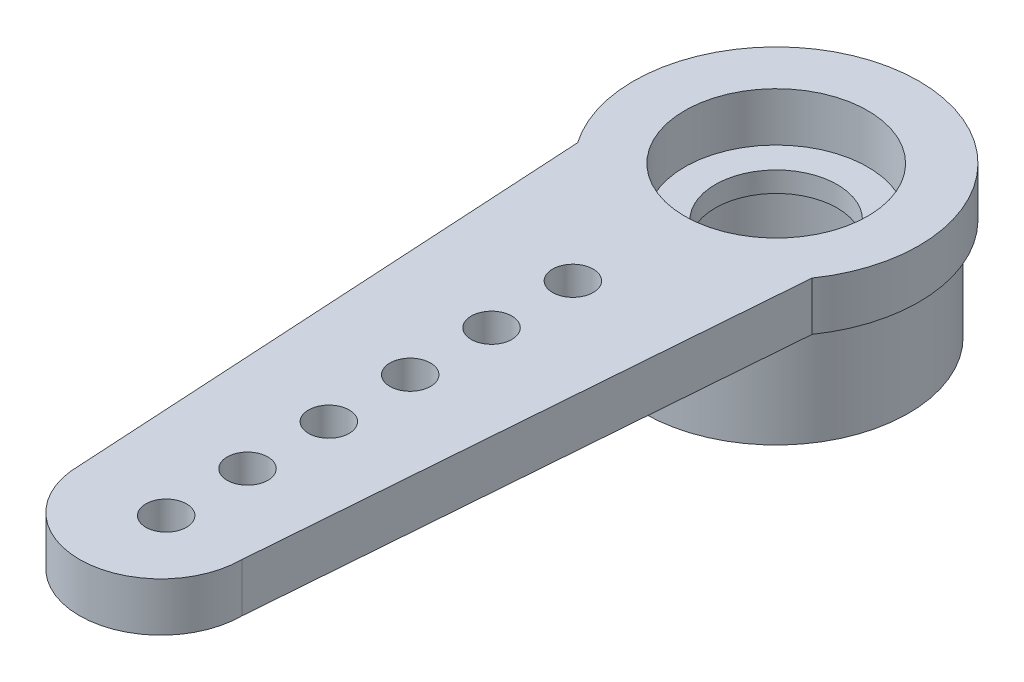
SolidWorks part; units mm, degrees
ref_plane "Front Plane" through (0, 0, 0) normal (0, 0, 1) x (1, 0, 0)
ref_plane "Top Plane" through (0, 0, 0) normal (0, 1, 0) x (1, 0, 0)
ref_plane "Right Plane" through (0, 0, 0) normal (1, 0, 0) x (0, 0, -1)
sketch "Sketch1" plane through (0, 0, 0) normal (0, 1, 0) x (1, 0, 0)
  line L0 (0, 0) -> (0, 17) construction
  line L3 (-2.8824, 2) -> (-2, 17)
  line L4 (2.8824, 2) -> (2, 17)
  line L5 (-3, 0) -> (3, 0) construction
  line L6 (-2.8824, -2) -> (-2.1324, -14.9994)
  line L7 (2.8824, -2) -> (1.8676, -15)
  line L8 (0, 0) -> (7, 0) construction
  line L9 (2.8824, 2) -> (7, 2)
  line L10 (2.8824, -2) -> (7, -2)
  line L11 (-2.8824, -2) -> (-7, -2)
  line L12 (-2.8824, 2) -> (-7, 2)
  arc A3 (2, 17) -> (-2, 17) centre (0, 17) ccw
  circle A4 centre (0, 5) radius 0.5
  circle A5 centre (0, 7) radius 0.5
  circle A6 centre (0, 9) radius 0.5
  circle A7 centre (0, 11) radius 0.5
  circle A8 centre (0, 13) radius 0.5
  circle A9 centre (0, 15) radius 0.5
  circle A10 centre (0, 17) radius 0.5
  circle A12 centre (0, -15) radius 0.5
  circle A13 centre (0, -13) radius 0.5
  circle A14 centre (0, -11) radius 0.5
  circle A15 centre (0, -9) radius 0.5
  circle A16 centre (0, -7) radius 0.5
  circle A17 centre (0, -5) radius 0.5
  arc A18 (1.8676, -15) -> (-2.1324, -14.9994) centre (-0.1324, -14.9994) cw
  arc A20 (7, -2) -> (7, 2) centre (7, 0) ccw
  circle A21 centre (7, 0) radius 0.5
  circle A22 centre (5, 0) radius 0.5
  circle A23 centre (-5, 0) radius 0.5
  circle A24 centre (-7, 0) radius 0.5
  arc A25 (-7, -2) -> (-7, 2) centre (-7, 0) cw
  circle A26 centre (0, 0) radius 2.25
  circle A27 centre (0, 0) radius 3.5083
  point P3 (0, 17.0297)
  point P38 (0, -17.0297)
  point P39 (3.5, 0)
  dimension "D2" = 2
  dimension "D5" = 1
  dimension "D8" = 2
  dimension "D10" = 1
  dimension "D11" = 1
  dimension "D13" = 4.5
  dimension "D15" = 2
  dimension "D1" = 1
  dimension "D3" = 17
  dimension "D4" = 1
  dimension "D6" = 5
  dimension "D9" = 7
  dimension "D12" = 2
  dimension "D14" = 15
  dimension "D16" = 0.75
  dimension "D7" = 7
extrude "Boss-Extrude1" add sketch "Sketch1" along normal blind 1.2 contours A27 L6 A18 L7 A16 A14 A12 A13 A15 A17 | A27 A26
sketch "Sketch2" plane through (0, 0, 0) normal (0, 1, 0) x (1, 0, 0)
  circle A2 centre (0, 0) radius 3.25
  circle A3 centre (0, 0) radius 1.5
  dimension "D1" = 6.5
  dimension "D2" = 3
extrude "Boss-Extrude2" add sketch "Sketch2" against normal blind 2.5
sketch "Sketch3" plane through (0, -2.5, 0) normal (0, -1, 0) x (1, 0, 0)
  circle A0 centre (0, 0) radius 2.5
  dimension "D1" = 5
extrude "Cut-Extrude1" cut sketch "Sketch3" against normal blind 2
